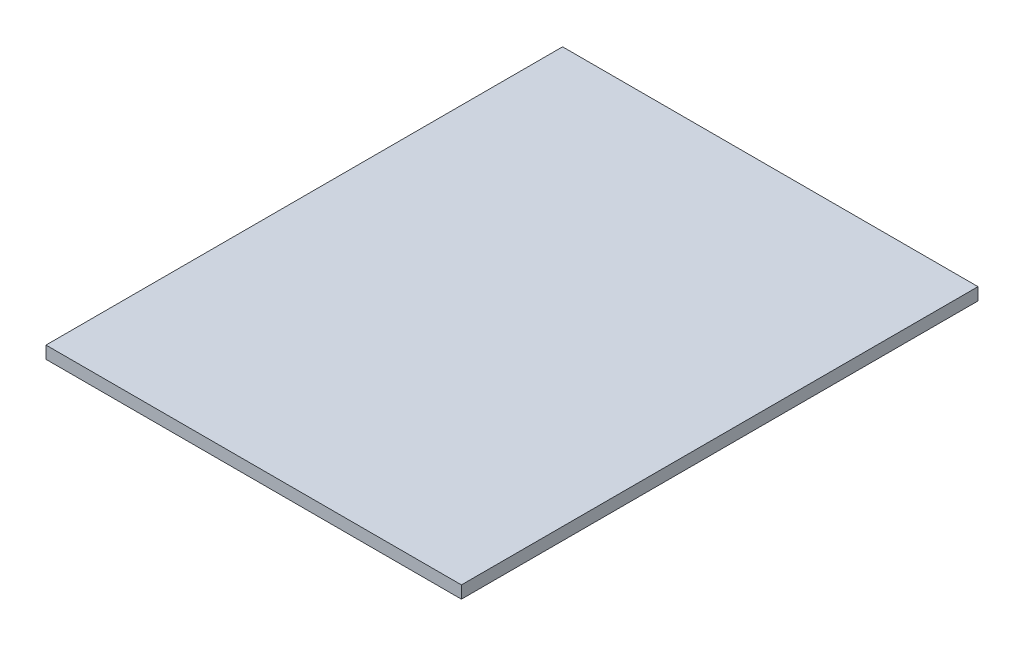
SolidWorks part; units mm, degrees
ref_plane "Front" through (0, 0, 0) normal (0, 0, 1) x (1, 0, 0)
ref_plane "Top" through (0, 0, 0) normal (0, 1, 0) x (1, 0, 0)
ref_plane "Right" through (0, 0, 0) normal (1, 0, 0) x (0, 0, -1)
sketch "Sketch1" plane through (0, 0, 0) normal (0, 1, 0) x (1, 0, 0)
  line L1 (-306.3875, -381) -> (306.3875, -381)
  line L2 (-306.3875, -381) -> (-306.3875, 381)
  line L3 (-306.3875, 381) -> (306.3875, 381)
  line L4 (306.3875, -381) -> (306.3875, 381)
  line L5 (-306.3875, -381) -> (306.3875, 381) construction
  line L6 (-306.3875, 381) -> (306.3875, -381) construction
  point P0 (0, 0)
  dimension "D1" = 612.775
  dimension "D2" = 762
extrude "Boss-Extrude1" add sketch "Sketch1" along normal blind 18.288
